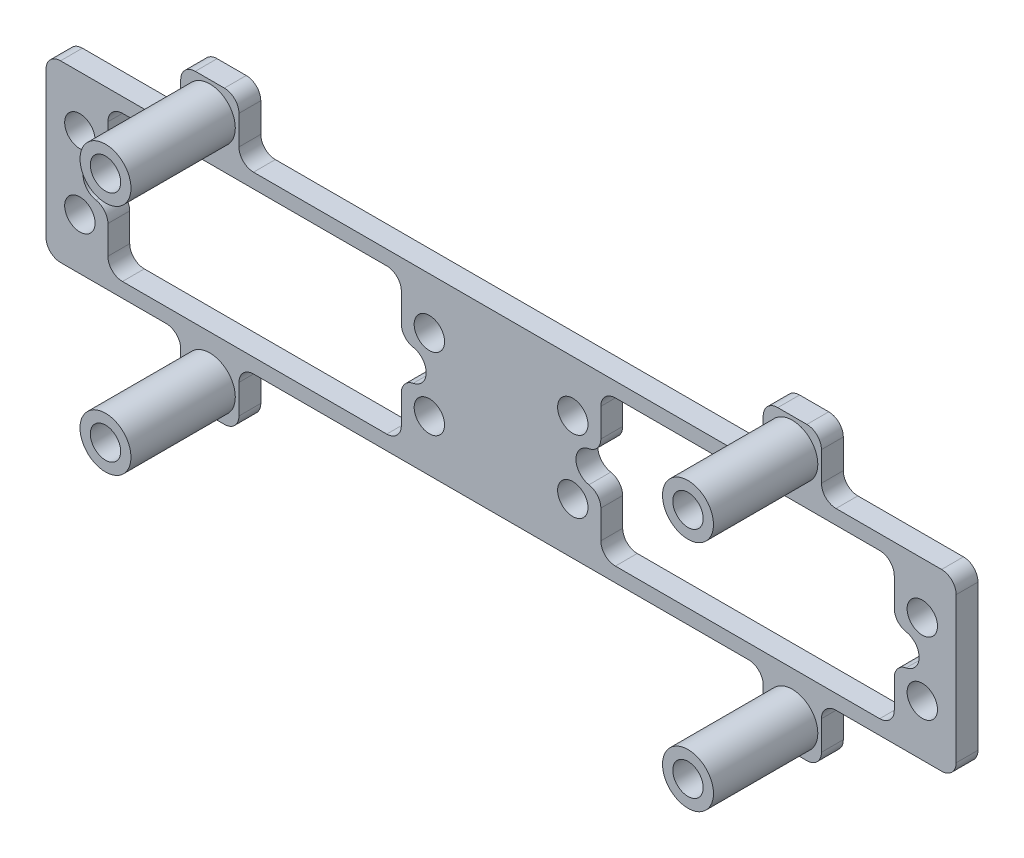
SolidWorks part; units mm, degrees
ref_plane "Front Plane" through (0, 0, 0) normal (0, 0, 1) x (1, 0, 0)
ref_plane "Top Plane" through (0, 0, 0) normal (0, 1, 0) x (1, 0, 0)
ref_plane "Right Plane" through (0, 0, 0) normal (1, 0, 0) x (0, 0, -1)
sketch "Sketch1" plane through (0, 0, 0) normal (0, 0, 1) x (1, 0, 0)
  line L0 (0, 0) -> (-50000, 0) construction
  line L1 (63, -18) -> (-63, -18) construction
  line L2 (63, -18) -> (63, 18) construction
  line L3 (63, 18) -> (-63, 18) construction
  line L4 (-63, -18) -> (-63, 18) construction
  line L5 (63, -18) -> (-63, 18) construction
  line L6 (63, 18) -> (-63, -18) construction
  line L7 (-40, 4.95) -> (-40, 16)
  line L8 (-57.85, 4.95) -> (-9.85, 4.95) construction
  line L9 (-57.85, 4.95) -> (-57.85, -4.95) construction
  line L10 (-57.85, -4.95) -> (-9.85, -4.95) construction
  line L11 (-9.85, 4.95) -> (-9.85, -4.95) construction
  line L12 (-57.85, 4.95) -> (-9.85, -4.95) construction
  line L13 (-57.85, -4.95) -> (-9.85, 4.95) construction
  line L14 (57.85, -4.95) -> (9.85, -4.95) construction
  line L15 (57.85, -4.95) -> (57.85, 4.95) construction
  line L16 (57.85, 4.95) -> (9.85, 4.95) construction
  line L17 (9.85, -4.95) -> (9.85, 4.95) construction
  line L18 (57.85, -4.95) -> (9.85, 4.95) construction
  line L19 (57.85, 4.95) -> (9.85, -4.95) construction
  line L20 (0, 0) -> (0, -50000) construction
  line L21 (40, 16) -> (40, -49984) construction
  line L22 (62.5, -12) -> (44, -12)
  line L23 (62.5, -12) -> (62.5, 12)
  line L24 (62.5, 12) -> (44, 12)
  line L25 (-62.5, -12) -> (-62.5, 12)
  line L26 (62.5, -12) -> (-62.5, 12) construction
  line L27 (62.5, 12) -> (-62.5, -12) construction
  line L28 (54, -10) -> (13.7, -10)
  line L29 (54, -10) -> (54, -2.1798)
  line L30 (54, 10) -> (13.7, 10)
  line L31 (13.7, -10) -> (13.7, -2.1798)
  line L32 (54, -10) -> (13.7, 10) construction
  line L33 (54, 10) -> (13.7, -10) construction
  line L34 (36, 12) -> (36, 20)
  line L35 (44, 12) -> (44, 20)
  line L36 (36, 20) -> (44, 20)
  line L37 (-54, 10) -> (-13.7, 10)
  line L38 (-13.7, -10) -> (-13.7, -2.1798)
  line L39 (-54, -10) -> (-13.7, -10)
  line L40 (-54, -10) -> (-54, -2.1798)
  line L41 (36, -12) -> (36, -20)
  line L42 (36, -20) -> (44, -20)
  line L43 (44, -12) -> (44, -20)
  line L44 (-36, 12) -> (-36, 20)
  line L45 (-36, 20) -> (-44, 20)
  line L46 (-44, 12) -> (-44, 20)
  line L47 (-36, -12) -> (-36, -20)
  line L48 (-36, -20) -> (-44, -20)
  line L49 (-44, -12) -> (-44, -20)
  line L50 (-44, -12) -> (-62.5, -12)
  line L51 (-44, 12) -> (-62.5, 12)
  line L52 (36, -12) -> (-36, -12)
  line L53 (36, 12) -> (-36, 12)
  line L54 (-55.2335, 0) -> (-51.6913, 0) construction
  line L55 (-55.2335, 2.1798) -> (-54, 2.1798)
  line L56 (-55.2335, -2.1798) -> (-54, -2.1798)
  line L57 (-54, 2.1798) -> (-54, 10)
  line L58 (-33.85, 0) -> (-33.85, -50000) construction
  line L59 (-12.4665, 2.1798) -> (-13.7, 2.1798)
  line L60 (-12.4665, -2.1798) -> (-13.7, -2.1798)
  line L61 (-13.7, 2.1798) -> (-13.7, 10)
  line L62 (55.2335, -2.1798) -> (54, -2.1798)
  line L63 (55.2335, 2.1798) -> (54, 2.1798)
  line L64 (12.4665, 2.1798) -> (13.7, 2.1798)
  line L65 (12.4665, -2.1798) -> (13.7, -2.1798)
  line L66 (13.7, 2.1798) -> (13.7, 10)
  line L67 (54, 2.1798) -> (54, 10)
  circle A0 centre (-40, 16) radius 2.0875
  circle A1 centre (-57.85, 4.95) radius 2.0875
  circle A2 centre (-57.85, -4.95) radius 2.0875
  circle A3 centre (-9.85, 4.95) radius 2.0875
  circle A4 centre (-9.85, -4.95) radius 2.0875
  circle A5 centre (-40, -16) radius 2.0875
  circle A6 centre (57.85, -4.95) radius 2.0875
  circle A7 centre (57.85, 4.95) radius 2.0875
  circle A8 centre (40, 16) radius 2.0875
  circle A9 centre (40, -16) radius 2.0875
  circle A10 centre (9.85, 4.95) radius 2.0875
  circle A11 centre (9.85, -4.95) radius 2.0875
  arc A12 (-55.2335, 2.1798) -> (-55.2335, -2.1798) centre (-55.2335, 0) ccw
  arc A14 (-12.4665, 2.1798) -> (-12.4665, -2.1798) centre (-12.4665, 0) cw
  arc A15 (55.2335, 2.1798) -> (55.2335, -2.1798) centre (55.2335, 0) cw
  arc A16 (12.4665, 2.1798) -> (12.4665, -2.1798) centre (12.4665, 0) ccw
  point P0 (0, 0)
  point P8 (-33.85, 0)
  point P13 (33.85, 0)
  point P37 (33.85, 0)
  point P40 (0, 0)
  point P71 (-53.4624, 0)
  dimension "D11" = 4.175
  dimension "D1" = 126
  dimension "D2" = 36
  dimension "D3" = 125
  dimension "D4" = 9.9
  dimension "D5" = 48
  dimension "D6" = 9.9
  dimension "D7" = 115.7
  dimension "D8" = 5.15
  dimension "D9" = 11.05
  dimension "D10" = 17.85
  dimension "D12" = 24
  dimension "D13" = 40.3
  dimension "D14" = 20
  dimension "D15" = 4
  dimension "D16" = 4
extrude "Boss-Extrude1" add sketch "Sketch1" along normal blind 3
fillet "Fillet1" radius 2 36 edges at (-54, -10, 1.5) (-13.7, -10, 1.5) (54, -10, 1.5) (13.7, -10, 1.5) (36, 12, 1.5) (36, 20, 1.5) (44, 20, 1.5) (62.5, -12, 1.5) (44, 12, 1.5) (62.5, 12, 1.5) (44, -20, 1.5) (44, -12, 1.5) (36, -20, 1.5) (36, -12, 1.5) (-36, -20, 1.5) (-36, -12, 1.5) (-44, -20, 1.5) (-62.5, -12, 1.5) (-44, -12, 1.5) (-62.5, 12, 1.5) (-44, 12, 1.5) (-44, 20, 1.5) (-36, 12, 1.5) (-36, 20, 1.5) (13.7, 2.1798, 1.5) (13.7, -2.1798, 1.5) (54, -2.1798, 1.5) (54, 2.1798, 1.5) (-13.7, -2.1798, 1.5) (-13.7, 2.1798, 1.5) (-54, -2.1798, 1.5) (-54, 2.1798, 1.5) (-54, 10, 1.5) (-13.7, 10, 1.5) (54, 10, 1.5) (13.7, 10, 1.5)
sketch "Sketch2" plane through (0, 0, 3) normal (0, 0, 1) x (1, 0, 0)
  circle A0 centre (-40, 16) radius 3.5
  circle A1 centre (-40, 16) radius 2.0875
  circle A2 centre (-40, -16) radius 2.0875
  circle A3 centre (-40, -16) radius 3.5
  circle A4 centre (40, -16) radius 3.5
  circle A5 centre (40, -16) radius 2.0875
  circle A6 centre (40, 16) radius 2.0875
  circle A7 centre (40, 16) radius 3.5
  point P4 (-40, 16)
  dimension "D1" = 7
extrude "Boss-Extrude2" add sketch "Sketch2" along normal blind 14.33 contours A1 | A0 | A3 | A2 | A4 | A5 | A7 | A6
